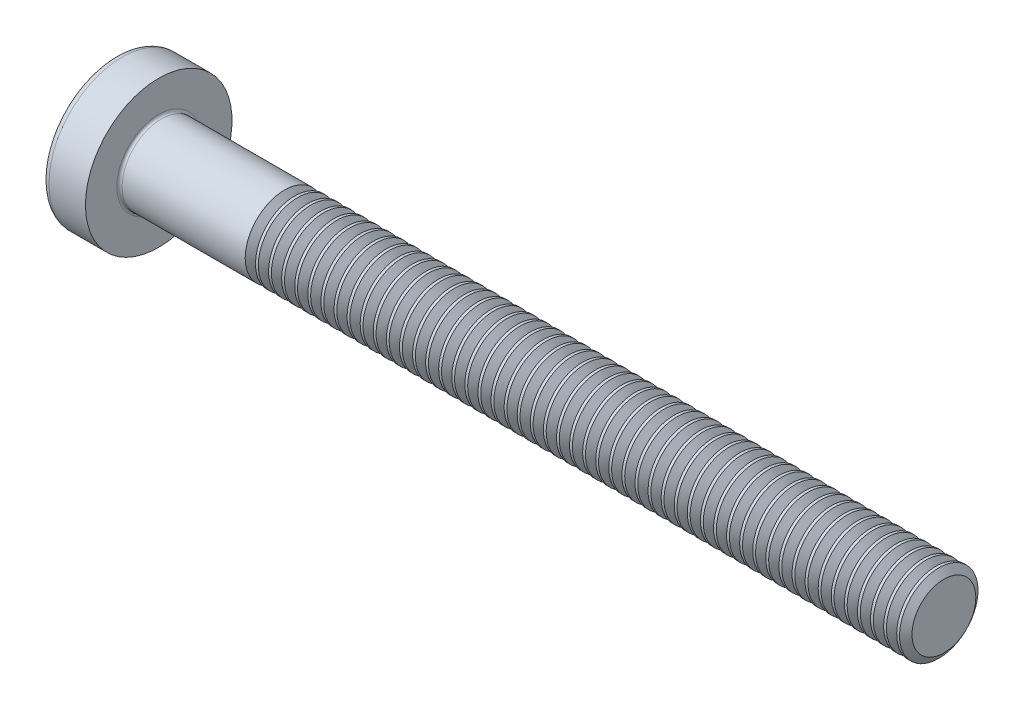
SolidWorks part; units mm, degrees
ref_plane "Plane1" through (0, 0, 0) normal (0, 0, 1) x (1, 0, 0)
ref_plane "Plane2" through (0, 0, 0) normal (0, 1, 0) x (1, 0, 0)
ref_plane "Plane3" through (0, 0, 0) normal (1, 0, 0) x (0, 0, -1)
sketch "BodySke" plane through (0, 0, 0) normal (0, 0, 1) x (1, 0, 0)
  line L0 (2.4, 1.5) -> (2.4, 2.8)
  line L1 (2.65, 6.35) -> (2.65, -3.175) construction
  line L2 (-25.4, 0) -> (127, 0) construction
  line L3 (32.4, 0) -> (0, 0)
  line L4 (2.4, 1.5) -> (32.4, 1.5)
  line L5 (32.4, 1.5) -> (32.4, 0)
  line L6 (1.0035, 2.8) -> (2.4, 2.8)
  line L8 (7.4, 6.35) -> (7.4, -3.175) construction
  arc A0 (0.7754, 2.6744) -> (0, 0) centre (5, 0) ccw
  arc A2 (0.7754, 2.6744) -> (1.0035, 2.8) centre (1.0035, 2.53) cw
  dimension "Head_crown_rad" = 5
  dimension "Head_fillet_rad" = 0.27
  dimension "Head_ht" = 2.4
  dimension "Head_dia" = 5.6
  dimension "Advance" = 0.5
  dimension "Diameter" = 3
revolve "Base-Revolve" add sketch "BodySke"
cosmetic thread "ThreadCosmetic" [suppressed]
fillet "Fillet1" radius 0.1 1 edges at (2.4, 0, 1.5)
sketch "Sketch3" plane through (0, 0, 0) normal (1, 0, 0) x (0, 0, -1)
  line L0 (0.37, -1.4) -> (-0.37, -1.4)
  line L1 (0.37, -1.4) -> (0.37, 1.4)
  line L2 (-0.37, 1.4) -> (0.37, 1.4)
  line L3 (-0.37, 1.4) -> (-0.37, -1.4)
  dimension "Cross_dia" = 2.8
  dimension "D1" = 1.4
  dimension "Cross_width" = 0.74
  dimension "D2" = 0.37
ref_plane "Plane4" through (1.75, 0, 0) normal (1, 0, 0) x (0, 0, -1)
sketch "Sketch4" plane through (1.75, 0, 0) normal (1, 0, 0) x (0, 0, -1)
  line L0 (0.37, -0.5275) -> (-0.37, -0.5275)
  line L1 (0.37, -0.5275) -> (0.37, 0.5275)
  line L2 (-0.37, 0.5275) -> (0.37, 0.5275)
  line L3 (-0.37, 0.5275) -> (-0.37, -0.5275)
  dimension "D1" = 0.74
  dimension "D2" = 1.055
  dimension "D3" = 0.37
  dimension "D4" = 0.5275
loft "Recess" cut profiles "Sketch3", "Sketch4"
pattern_circular "RecPat" count 2 every 90 about axis through (0, 0, 0) along (1, 0, 0) of "Recess"
sketch "RecCorSke" plane through (0, 0, 0) normal (0, 0, 1) x (1, 0, 0)
  line L0 (-3.175, 0) -> (15.875, 0) construction
  line L1 (-25.4, 0) -> (127, 0) construction
  line L2 (0, 0) -> (0, 0.6784)
  line L3 (0, 0.6784) -> (1.75, 0.556)
  line L4 (1.75, 0.556) -> (1.9307, 0)
  line L5 (1.9307, 0) -> (0, 0)
  dimension "Diameter" = 1.112
  dimension "Depth" = 1.75
  dimension "Draft_angle" = 4
  dimension "Bottom_angle" = 18
revolve "RecessCore" cut sketch "RecCorSke" angle 360 about L0
sketch "ThdSchSke" plane through (0, 0, 0) normal (0, 0, 1) x (1, 0, 0)
  line L0 (7.4, -1.2195) -> (7.2036, -1.5)
  line L1 (7.4, -1.2195) -> (7.5964, -1.5)
  line L2 (7.5964, -1.5) -> (7.5964, -1.875)
  line L3 (-3.175, 0) -> (5.1513, 0) construction
  line L5 (7.5964, -1.875) -> (7.2036, -1.875)
  line L6 (7.2036, -1.875) -> (7.2036, -1.5)
  dimension "Diameter" = 3
  dimension "SideAngle" = 55
  dimension "VeeAngle" = 70
  dimension "Thread_minor" = 2.439
  dimension "Overcut" = 3.75
revolve "ThreadSchematic" cut sketch "ThdSchSke" angle 360 about L3
pattern_linear "ThdSchPat" count 51 spacing 0.5 along (1, 0, 0) of "ThreadSchematic"
equation "\"D1@Sketch3\" = \"Cross_dia@Sketch3\" / 2"
equation "\"D2@Sketch3\" = \"Cross_width@Sketch3\" / 2"
equation "\"Depth@RecCorSke\" = \"Cross_depth@Plane4\""
equation "\"D1@Sketch4\" = \"Cross_width@Sketch3\""
equation "\"D2@Sketch4\" = \"Cross_dia@Sketch3\" - 2.0 * \"Cross_depth@Plane4\" * tan(26.5  * 0.017453292)"
equation "\"D3@Sketch4\" = \"D1@Sketch4\" / 2"
equation "\"D4@Sketch4\" = \"D2@Sketch4\" / 2"
equation "\"Thread_length@ThreadCosmetic\" = ((sgn( (\"Length@BodySke\" - \"Advance@BodySke\" * 2.0 ) - \"Thread_nom@BodySke\" )-1)*( (\"Length@BodySke\" - \"Advance@BodySke\" * 2.0 ) - \"Thread_nom@BodySke\" ))/-2+ \"Thread_nom@BodySke\""
equation "\"Thread_minor@ThdSchSke\" = \"Thread_minor@ThreadCosmetic\""
equation "\"Diameter@ThdSchSke\" = \"Diameter@BodySke\""
equation "\"Overcut@ThdSchSke\" = \"Diameter@BodySke\" * 1.25"
equation "\"Start@ThdSchSke\" = \"Head_ht@BodySke\" + \"Length@BodySke\" - \"Thread_length@ThreadCosmetic\"  '---Non-countersunk---"
equation "\"Num_threads@ThdSchPat\" = int( \"Thread_length@ThreadCosmetic\" / \"Advance@BodySke\" + 0.999 )  + 1"
equation "\"Advance@ThdSchPat\" = \"Thread_length@ThreadCosmetic\" /  (\"Num_threads@ThdSchPat\" - 1) 'relax it"
